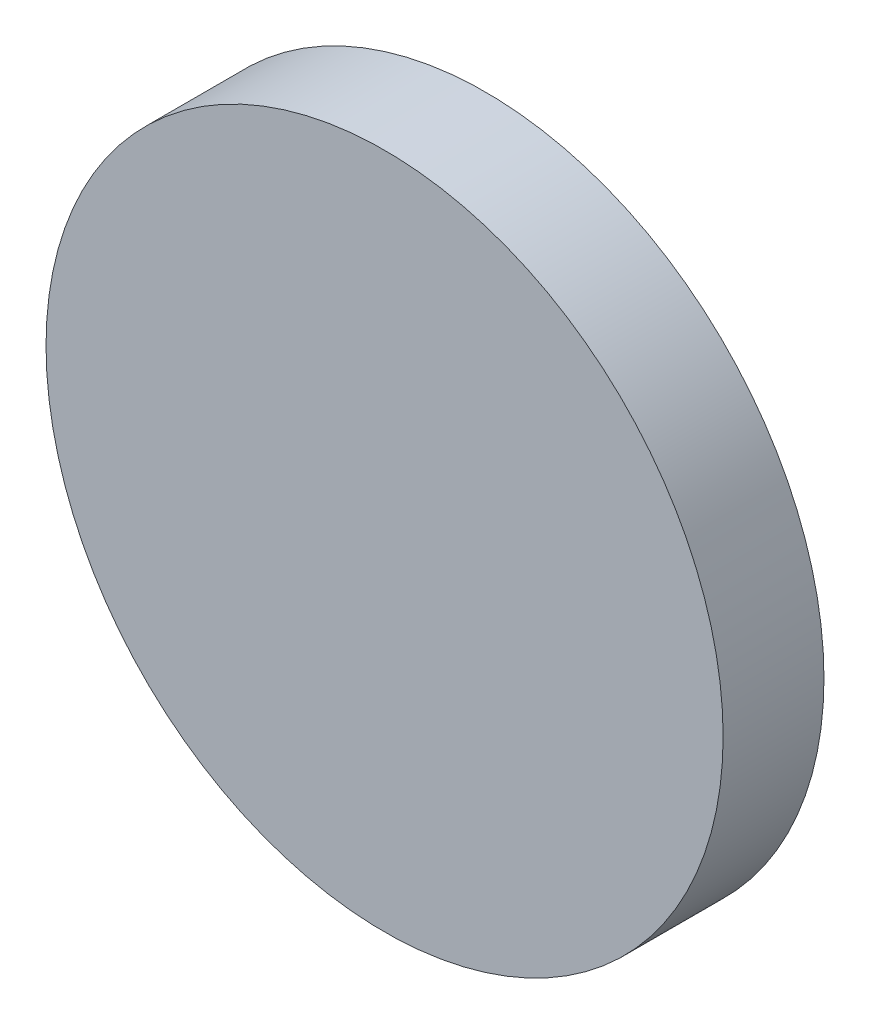
SolidWorks part; units mm, degrees
ref_plane "Front Plane" through (0, 0, 0) normal (0, 0, 1) x (1, 0, 0)
ref_plane "Top Plane" through (0, 0, 0) normal (0, 1, 0) x (1, 0, 0)
ref_plane "Right Plane" through (0, 0, 0) normal (1, 0, 0) x (0, 0, -1)
sketch "Sketch1" plane through (0, 0, 0) normal (0, 0, 1) x (1, 0, 0)
  circle A0 centre (0, 0) radius 28.2
  dimension "D1" = 56.4
extrude "Boss-Extrude1" add sketch "Sketch1" along normal blind 8.4
